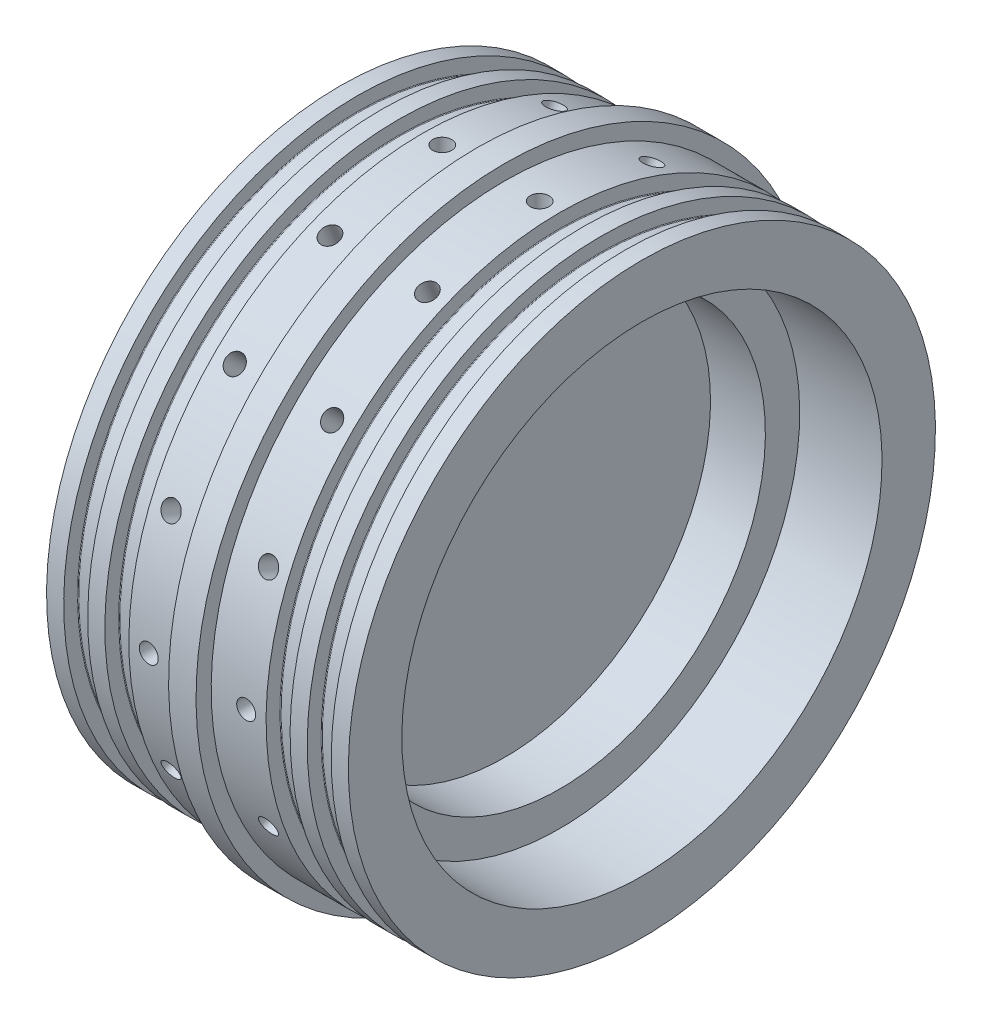
SolidWorks part; units mm, degrees
material "6061 Alloy"
ref_plane "Front Plane" through (0, 0, 0) normal (0, 0, 1) x (1, 0, 0)
ref_plane "Top Plane" through (0, 0, 0) normal (0, 1, 0) x (1, 0, 0)
ref_plane "Right Plane" through (0, 0, 0) normal (1, 0, 0) x (0, 0, -1)
sketch "Sketch4" plane through (0, 0, 0) normal (0, 0, 1) x (1, 0, 0)
  line L0 (0, 0) -> (0, 57.15)
  line L1 (0, 57.15) -> (5.08, 57.15)
  line L2 (5.08, 57.15) -> (5.08, 54.3433)
  line L3 (5.08, 54.3433) -> (15.24, 54.3433)
  line L4 (15.24, 54.3433) -> (15.24, 51.7906)
  line L5 (15.367, 51.6636) -> (19.558, 51.6636)
  line L6 (19.685, 51.7906) -> (19.685, 54.3433)
  line L7 (19.685, 54.3433) -> (22.86, 54.3433)
  line L8 (22.86, 54.3433) -> (22.86, 51.7906)
  line L9 (22.987, 51.6636) -> (27.178, 51.6636)
  line L10 (27.305, 51.7906) -> (27.305, 54.3433)
  line L11 (27.305, 54.3433) -> (30.48, 54.3433)
  line L12 (30.48, 54.3433) -> (30.48, 0)
  line L13 (30.48, 0) -> (0, 0)
  line L14 (15.24, 54.3433) -> (19.685, 54.3433) construction
  line L15 (22.86, 54.3433) -> (27.305, 54.3433) construction
  arc A0 (15.24, 51.7906) -> (15.367, 51.6636) centre (15.367, 51.7906) ccw
  arc A1 (19.685, 51.7906) -> (19.558, 51.6636) centre (19.558, 51.7906) cw
  arc A2 (22.86, 51.7906) -> (22.987, 51.6636) centre (22.987, 51.7906) ccw
  arc A3 (27.305, 51.7906) -> (27.178, 51.6636) centre (27.178, 51.7906) cw
  point P17 (15.24, 51.6636)
  point P21 (19.685, 51.6636)
  dimension "D9" = 0.127
  dimension "D2" = 5.08
  dimension "D5" = 10.16
  dimension "D7" = 4.445
  dimension "D4" = 3.175
  dimension "D6" = 57.15
  dimension "D3" = 3.175
  dimension "D1" = 54.3433
  dimension "D8" = 51.6636
revolve "Revolve1" add sketch "Sketch4" angle 360 about L13
sketch3d "3DSketch3"
  circle A0 centre (11.24, 0, 54.3433) radius 1.5
  circle A1 centre (15.24, 0, 0) radius 54.3433 construction
  point P2 (11.24, 0, 55.8433)
  point P5 (69.5833, 0, 0)
  point P6 (15.24, 0, 54.3433)
  point P7 (15.24, 0, 54.3433)
  dimension "D1" = 3
  dimension "D2" = 4
hole_wizard "#6-32 Tapped Hole1" positions "3DSketch4" profile "Sketch5" tap size "#6-32" standard "ANSI Inch"
sketch3d "3DSketch4"
  line L0 (11.557, 0, 54.3433) -> (15.24, 0, 54.3433) construction
  line L2 (11.557, 0, 54.3433) -> (5.08, 0, 54.3433) construction
  circle A1 centre (15.24, 0, 0) radius 54.3433 construction
  circle A2 centre (5.08, 0, 0) radius 54.3433 construction
  circle A3 centre (11.557, 0, 54.3433) radius 1.905 construction
  point P10 (11.557, 0, 54.3433)
  point P18 (69.5833, 0, 0)
  point P24 (59.4233, 0, 0)
  point P27 (11.557, 0, 56.2483)
  dimension "D1" = 3.81
  dimension "D2" = 6.477
sketch "Sketch5" plane through (11.557, 0, 54.3433) normal (1, 0, 0) x (0, -1, 0)
  line L0 (0, 0) -> (0, 10.9727)
  line L1 (0, 10.9727) -> (1.3525, 10.16)
  line L2 (1.3525, 10.16) -> (1.3525, 7.62)
  line L3 (1.3525, 7.62) -> (1.7526, 7.62)
  line L4 (1.7526, 7.62) -> (1.7526, 0)
  line L5 (1.7526, 0) -> (0, 0)
  line L10 (0, 10.9727) -> (-1.3526, 10.16) construction
  line L11 (0, -6.35) -> (0, 107.95) construction
  dimension "Tap Drill Dia." = 2.7051
  dimension "Tap Drill Depth" = 10.16
  dimension "Thread Major Dia." = 3.5052
  dimension "Thread Depth" = 7.62
  dimension "Drill Angle" = 118
sketch "Sketch6" plane through (0, 0, 0) normal (-1, 0, 0) x (0, 0, 1)
  circle A0 centre (0, 0) radius 54.3433
  dimension "D1" = 108.6866
ref_plane "Plane2" through (2.54, 0, 0) normal (1, 0, 0) x (0, 0, -1)
sketch "Sketch8" plane through (30.48, 0, 0) normal (1, 0, 0) x (0, 0, -1)
  circle A0 centre (0, 0) radius 44.45
  dimension "D1" = 88.9
extrude "Cut-Extrude1" cut sketch "Sketch8" against normal up to surface (15.24 mm away) up to face at (15.24, 54.3433, 0)
sketch "Sketch15" plane through (15.24, 0, 0) normal (1, 0, 0) x (0, 0, -1)
  circle A0 centre (0, 0) radius 38.1
extrude "Cut-Extrude2" cut sketch "Sketch15" against normal up to surface (10.16 mm away) up to face at (5.08, 57.15, 0)
ref_plane "Plane3" through (2.54, 0, 0) normal (-1, 0, 0) x (0, 0, 1)
mirror "Mirror1" about plane through (2.54, 0, 0) normal (-1, 0, 0) of "Revolve1", "Cut-Extrude1", "Cut-Extrude2"
mirror "Mirror2" about plane through (2.54, 0, 0) normal (-1, 0, 0) of "#6-32 Tapped Hole1"
pattern_circular "CirPattern1" count 16 over 360 about axis through (0, 0, 0) along (1, 0, 0) of "#6-32 Tapped Hole1"
pattern_circular "CirPattern2" count 16 over 360 about axis through (0, 0, 0) along (1, 0, 0) of "Mirror2"
equation "\"D8@Sketch4\"=4.068in/2"
equation "\"D9@Sketch4\"=.005in"
equation "\"D1@Sketch4\"=4.279in/2"
equation "\"D1@Sketch6\"=4.279IN"
